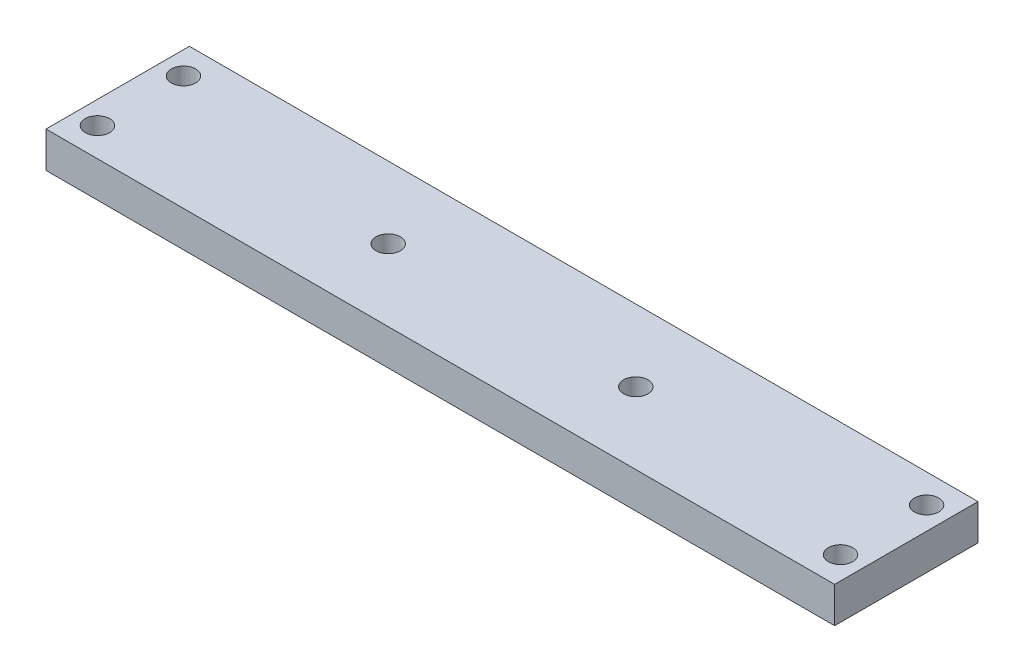
SolidWorks part; units mm, degrees
ref_plane "Front Plane" through (0, 0, 0) normal (0, 0, 1) x (1, 0, 0)
ref_plane "Top Plane" through (0, 0, 0) normal (0, 1, 0) x (1, 0, 0)
ref_plane "Right Plane" through (0, 0, 0) normal (1, 0, 0) x (0, 0, -1)
sketch "Sketch1" plane through (0, 0, 0) normal (0, 1, 0) x (1, 0, 0)
  line L5 (-55, -10) -> (55, -10)
  line L6 (-55, -10) -> (-55, 10)
  line L7 (-55, 10) -> (55, 10)
  line L8 (55, -10) -> (55, 10)
  line L9 (0, 10) -> (0, -10) construction
  line L10 (-55, 0) -> (55, 0) construction
  point P0 (0, 0)
  dimension "D1" = 20
  dimension "D2" = 110
extrude "Boss-Extrude1" add sketch "Sketch1" along normal mid plane 5
sketch "Sketch2" plane through (0, 2.5, 0) normal (0, 1, 0) x (1, 0, 0)
  line L0 (0, 10) -> (0, -10) construction
  line L1 (55, 10) -> (-55, 10) construction
  line L2 (-55, -10) -> (55, -10) construction
  line L3 (-55, 0) -> (55, 0) construction
  line L4 (-55, 10) -> (-55, -10) construction
  line L5 (55, -10) -> (55, 10) construction
  point P12 (-51.825, -6)
  point P14 (51.825, -6)
  point P16 (-51.825, 6)
  point P17 (51.825, 6)
  point P18 (17.275, 0)
  point P23 (-17.275, 0)
  dimension "D1" = 103.65
  dimension "D2" = 4
  dimension "D3" = 34.55
  dimension "D4" = 34.55
hole_wizard "M3 Clearance Hole1" positions "Sketch2" profile "Sketch3" hole size "M3" standard "ANSI Metric" end condition through all
sketch "Sketch3" plane through (-17.275, 2.5, 0) normal (1, 0, 0) x (0, 0, 1)
  line L0 (0, 0) -> (0, 5)
  line L1 (0, 5) -> (1.7, 5)
  line L2 (1.7, 5) -> (1.7, 0)
  line L5 (1.7, 0) -> (0, 0)
  line L11 (0, -6.35) -> (0, 107.95) construction
  dimension "Thru Hole Dia." = 3.4
  dimension "Thru Hole Depth" = 5
